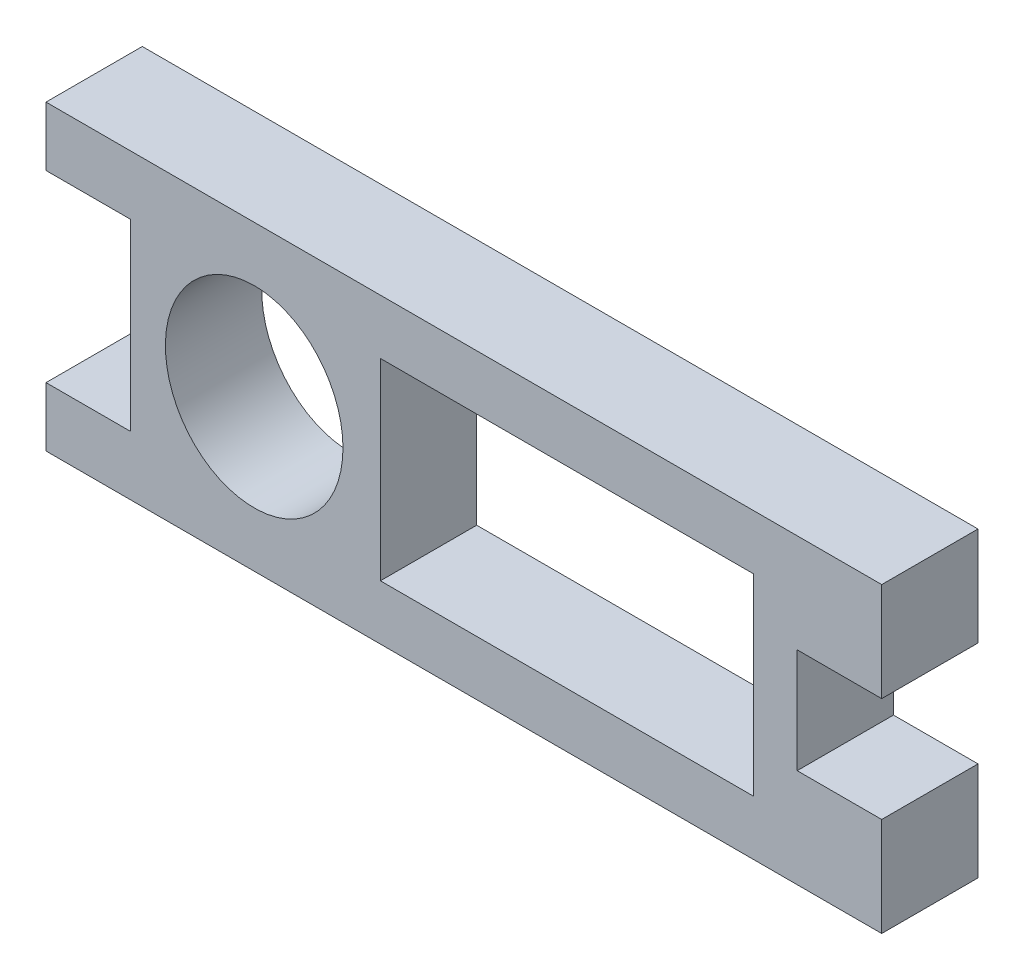
SolidWorks part; units mm, degrees
material "Acrylic (Medium-high impact)"
ref_plane "Front Plane" through (0, 0, 0) normal (0, 0, 1) x (1, 0, 0)
ref_plane "Top Plane" through (0, 0, 0) normal (0, 1, 0) x (1, 0, 0)
ref_plane "Right Plane" through (0, 0, 0) normal (1, 0, 0) x (0, 0, -1)
sketch "Sketch1" plane through (0, 0, 0) normal (0, 0, 1) x (1, 0, 0)
  line L0 (717.4092, 382.5577) -> (717.4092, 393.7158)
  line L1 (738.1592, 380.8428) -> (738.1592, 396.1306) construction
  line L2 (717.4092, 378.9577) -> (757.9092, 378.9577)
  line L3 (755.2592, 382.2867) -> (738.1592, 382.2867)
  line L4 (763.0434, 397.3158) -> (757.9092, 397.3158)
  line L5 (717.4092, 397.3158) -> (757.9092, 397.3158)
  line L6 (763.0434, 384.9577) -> (757.9092, 384.9577)
  line L7 (712.275, 393.7158) -> (717.4092, 393.7158)
  line L8 (763.0434, 378.9577) -> (763.0434, 384.9577)
  line L9 (763.0434, 378.9577) -> (757.9092, 378.9577)
  line L10 (712.275, 397.3158) -> (712.275, 393.7158)
  line L12 (717.4092, 378.9577) -> (712.275, 378.9577)
  line L13 (712.275, 378.9577) -> (712.275, 382.5577)
  line L14 (712.275, 382.5577) -> (717.4092, 382.5577)
  line L15 (717.4092, 397.3158) -> (712.275, 397.3158)
  line L17 (763.0434, 397.3158) -> (763.0434, 391.3158)
  line L18 (763.0434, 391.3158) -> (757.9092, 391.3158)
  line L19 (757.9092, 384.9577) -> (757.9092, 391.3158)
  line L20 (717.4107, 388.1367) -> (-49282.5893, 388.1367) construction
  line L21 (755.2592, 382.2867) -> (755.2592, 393.9867)
  line L22 (738.1592, 382.2867) -> (732.5897, 382.2867)
  line L23 (732.5897, 393.9867) -> (732.5897, 382.2867)
  line L24 (755.2592, 393.9867) -> (738.1592, 393.9867)
  line L25 (738.1592, 393.9867) -> (732.5897, 393.9867)
  line L26 (732.6592, 388.1367) -> (717.4092, 388.1367) construction
  line L31 (732.6592, 390.7223) -> (755.2592, 390.7223) construction
  ellipse E0 centre (724.9224, 388.1367) end of major axis (724.9224, 393.9867) minor radius 5.3936
  point P2 (732.6592, 388.1367)
  point P5 (717.4092, 388.1367)
  point P7 (717.4092, 388.1367)
  point P37 (755.2592, 388.1367)
  point P44 (755.2592, 388.1367)
  point P45 (732.4277, 388.1367)
  dimension "D1" = 11.7
  dimension "D2" = 3.6
  dimension "D3" = 6
  dimension "D4" = 18.3581
  dimension "D5" = 40.5
  dimension "D6" = 5.1342
  dimension "D7" = 22.6695
extrude "Boss-Extrude1" add sketch "Sketch1" along normal blind 5.85
